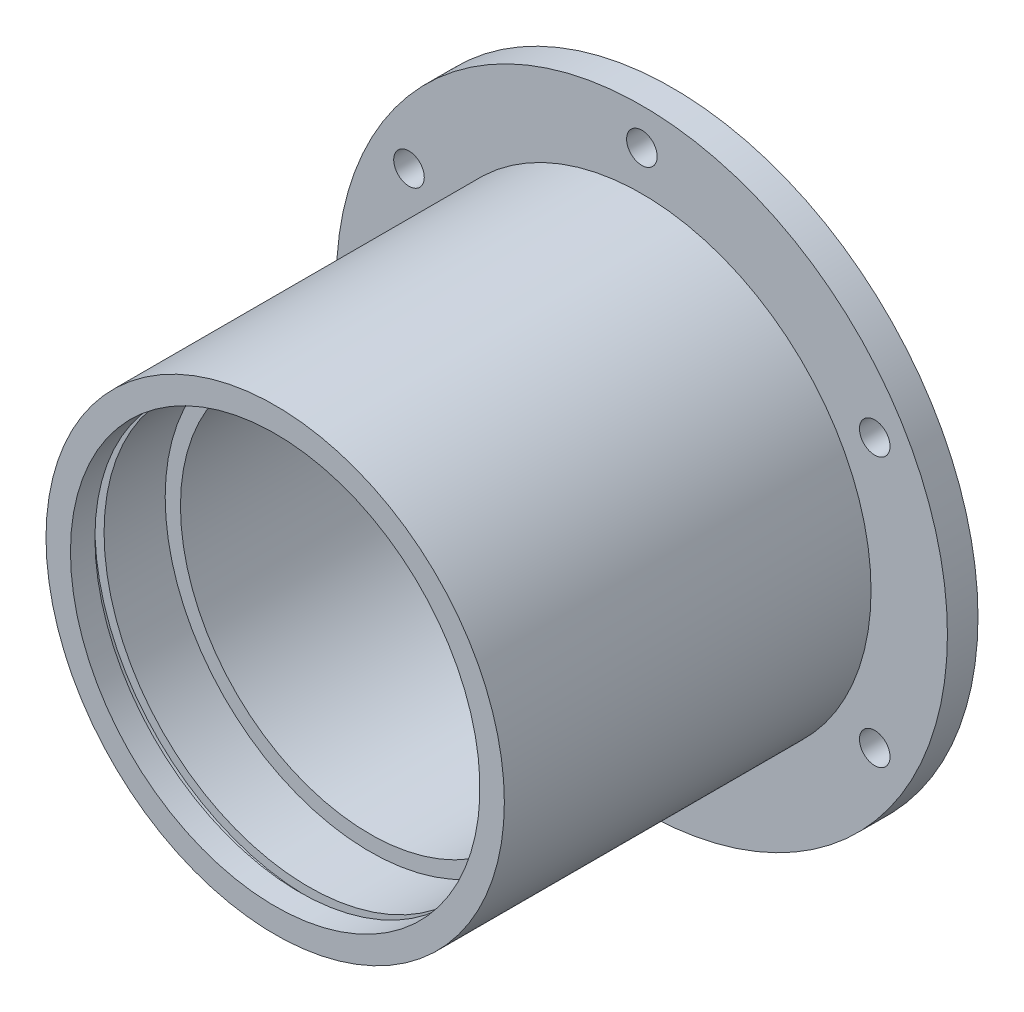
SolidWorks part; units mm, degrees
ref_plane "Front Plane" through (0, 0, 0) normal (0, 0, 1) x (1, 0, 0)
ref_plane "Top Plane" through (0, 0, 0) normal (0, 1, 0) x (1, 0, 0)
ref_plane "Right Plane" through (0, 0, 0) normal (1, 0, 0) x (0, 0, -1)
sketch "Sketch1" plane through (0, 0, 0) normal (0, 0, 1) x (1, 0, 0)
  line L0 (0, 44) -> (0, 0) construction
  circle A0 centre (0, 0) radius 50
  circle A1 centre (0, 44) radius 2.5
  circle A2 centre (38.1051, 22) radius 2.5
  circle A3 centre (38.1051, -22) radius 2.5
  circle A4 centre (0, -44) radius 2.5
  circle A5 centre (-38.1051, -22) radius 2.5
  circle A6 centre (-38.1051, 22) radius 2.5
  point P18 (0, 0)
  dimension "D1" = 100
  dimension "D2" = 44
  dimension "D3" = 6
extrude "Boss-Extrude1" add sketch "Sketch1" along normal blind 5
sketch "Sketch2" plane through (0, 0, 5) normal (0, 0, 1) x (1, 0, 0)
  circle A0 centre (0, 0) radius 37.5
  circle A1 centre (0, 0) radius 33.5
  dimension "D1" = 75
  dimension "D2" = 67
extrude "Boss-Extrude2" add sketch "Sketch2" along normal blind 60
sketch "Sketch3" plane through (0, 0, 0) normal (0, 0, -1) x (-1, 0, 0)
  circle A0 centre (0, 0) radius 33.5
  dimension "D1" = 67
extrude "Cut-Extrude1" cut sketch "Sketch3" against normal blind 50
ref_plane "Plane1" through (0, 0, 32.5) normal (0, 0, -1) x (-1, 0, 0)
sketch "Sketch5" plane through (0, 0, 32.5) normal (0, 0, -1) x (-1, 0, 0)
  circle A0 centre (0, 0) radius 35
  circle A1 centre (0, 0) radius 31
  dimension "D1" = 62
  dimension "D2" = 70
extrude "Boss-Extrude4" add sketch "Sketch5" along normal blind 17 and the other way blind 17
sketch "Sketch6" plane through (0, 0, 15.5) normal (0, 0, -1) x (-1, 0, 0)
  circle A0 centre (0, 0) radius 34.5
  dimension "D1" = 69
extrude "Cut-Extrude2" cut sketch "Sketch6" along normal offset from surface (1.5 mm away) 4 from offset 10 up to face at (-33.5, 0, 0)
sketch "Sketch7" plane through (0, 0, 49.5) normal (0, 0, 1) x (1, 0, 0)
  circle A0 centre (0, 0) radius 35
  dimension "D1" = 70
extrude "Cut-Extrude3" cut sketch "Sketch7" along normal offset from surface (1.5 mm away) 4 from offset 10 up to face at (37.5, 0, 65)
